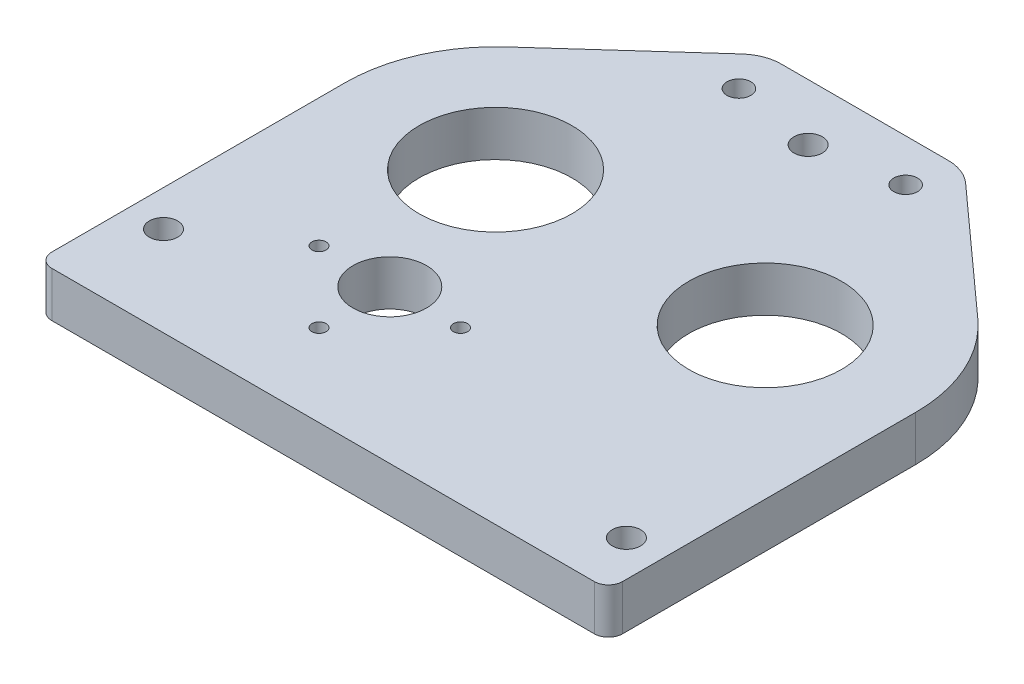
SolidWorks part; units mm, degrees
material "6061-T6 (SS)"
ref_plane "Front Plane" through (0, 0, 0) normal (0, 0, 1) x (1, 0, 0)
ref_plane "Top Plane" through (0, 0, 0) normal (0, 1, 0) x (1, 0, 0)
ref_plane "Right Plane" through (0, 0, 0) normal (1, 0, 0) x (0, 0, -1)
sketch "MasterSketch" plane through (0, 0, 0) normal (0, 1, 0) x (1, 0, 0)
  line L0 (-43.6583, 78.9815) -> (-8.5725, 27.2588) construction
  line L1 (-37.4522, 83.1914) -> (-2.3664, 31.4687)
  line L2 (-49.8644, 74.7716) -> (-14.7786, 23.0489)
  line L3 (15.24, 26.2031) -> (15.24, 177.1934) construction
  line L6 (-57.2127, 102.5887) -> (-52.8306, 72.5887)
  line L7 (-52.8306, 72.5887) -> (-3.3556, 79.8154)
  line L8 (-3.3556, 79.8154) -> (-14.1957, 154.0279)
  line L9 (-14.1957, 154.0279) -> (-57.2127, 102.5887)
  line L10 (-16.4304, 100.1391) -> (0.5118, 61.162) construction
  line L11 (-9.5528, 103.1286) -> (7.3895, 64.1515)
  line L12 (-23.308, 97.1496) -> (-6.3658, 58.1725)
  line L13 (74.1383, 78.9815) -> (39.0525, 27.2588) construction
  line L16 (-8.5725, 27.2588) -> (39.0525, 27.2588)
  line L17 (0, 0) -> (39.0525, 27.2588) construction
  line L18 (-8.5725, 27.2588) -> (0, 0) construction
  line L19 (-8.5725, 27.2588) -> (0.5118, 61.162) construction
  line L20 (67.9322, 83.1914) -> (32.8464, 31.4687)
  line L21 (-53.5533, 77.5362) -> (-43.6583, 78.9815) construction
  line L24 (-43.6583, 78.9815) -> (-42.9356, 74.034) construction
  line L25 (-6.5354, 101.5844) -> (-16.4304, 100.1391) construction
  line L26 (-16.4304, 100.1391) -> (-13.2506, 78.3701) construction
  line L27 (80.3444, 74.7716) -> (45.2586, 23.0489)
  line L28 (46.9104, 100.1391) -> (29.9682, 61.162) construction
  line L29 (40.0328, 103.1286) -> (23.0905, 64.1515)
  line L30 (53.788, 97.1496) -> (36.8458, 58.1725)
  line L31 (44.6757, 154.0279) -> (87.6927, 102.5887)
  line L32 (46.9104, 100.1391) -> (43.7306, 78.3701) construction
  line L33 (74.1383, 78.9815) -> (73.4156, 74.034) construction
  line L34 (84.0333, 77.5362) -> (74.1383, 78.9815) construction
  line L35 (33.8356, 79.8154) -> (44.6757, 154.0279)
  line L36 (83.3106, 72.5887) -> (33.8356, 79.8154)
  line L37 (87.6927, 102.5887) -> (83.3106, 72.5887)
  line L38 (0, 0) -> (0, -12.5) construction
  line L39 (-5.8229, 22.4963) -> (-3.0732, 27.2588)
  line L40 (-3.0732, 27.2588) -> (-5.8229, 32.0213)
  line L41 (-5.8229, 32.0213) -> (-11.3221, 32.0213)
  line L42 (-11.3221, 32.0213) -> (-14.0718, 27.2588)
  line L43 (-14.0718, 27.2588) -> (-11.3221, 22.4963)
  line L44 (-11.3221, 22.4963) -> (-5.8229, 22.4963)
  line L45 (36.3029, 32.0213) -> (33.5532, 27.2588)
  line L46 (33.5532, 27.2588) -> (36.3029, 22.4963)
  line L47 (36.3029, 22.4963) -> (41.8021, 22.4963)
  line L48 (41.8021, 22.4963) -> (44.5518, 27.2588)
  line L49 (44.5518, 27.2588) -> (41.8021, 32.0213)
  line L50 (41.8021, 32.0213) -> (36.3029, 32.0213)
  circle A0 centre (0, 0) radius 4.7625
  circle A1 centre (-8.5725, 27.2588) radius 23.8125
  circle A2 centre (39.0525, 27.2588) radius 23.8125
  arc A4 (-37.4522, 83.1914) -> (-49.8644, 74.7716) centre (-43.6583, 78.9815) ccw
  arc A5 (-14.7786, 23.0489) -> (-2.3664, 31.4687) centre (-8.5725, 27.2588) ccw
  arc A8 (-9.5528, 103.1286) -> (-23.308, 97.1496) centre (-16.4304, 100.1391) ccw
  arc A9 (-6.3658, 58.1725) -> (7.3895, 64.1515) centre (0.5118, 61.162) ccw
  circle A14 centre (-43.6583, 78.9815) radius 2.5
  circle A15 centre (-16.4304, 100.1391) radius 2.5
  arc A16 (67.9322, 83.1914) -> (80.3444, 74.7716) centre (74.1383, 78.9815) cw
  arc A17 (45.2586, 23.0489) -> (32.8464, 31.4687) centre (39.0525, 27.2588) cw
  arc A18 (40.0328, 103.1286) -> (53.788, 97.1496) centre (46.9104, 100.1391) cw
  arc A19 (36.8458, 58.1725) -> (23.0905, 64.1515) centre (29.9682, 61.162) cw
  circle A20 centre (46.9104, 100.1391) radius 2.5
  circle A21 centre (74.1383, 78.9815) radius 2.5
  circle A22 centre (0, 0) radius 17.5
  circle A23 centre (0, 0) radius 1.5875
  circle A24 centre (-8.5725, 27.2588) radius 4.7625 construction
  circle A25 centre (39.0525, 27.2588) radius 4.7625 construction
  circle A26 centre (0.5118, 61.162) radius 2.5
  circle A27 centre (29.9682, 61.162) radius 2.5
  circle A28 centre (-8.5725, 27.2588) radius 24.5999 construction
  circle A29 centre (39.0525, 27.2588) radius 24.5999 construction
  circle A30 centre (-8.5725, 27.2588) radius 13.5001
  circle A31 centre (39.0525, 27.2588) radius 13.5001
  circle A32 centre (0, 0) radius 12.5 construction
  circle A33 centre (0, -12.5) radius 1.25
  circle A34 centre (-12.5, 0) radius 1.25
  circle A35 centre (0, 12.5) radius 1.25
  circle A36 centre (12.5, 0) radius 1.25
  circle A37 centre (-8.5725, 27.2588) radius 5.4993 construction
  point P9 (-26.1154, 53.1202)
  point P17 (56.5954, 53.1202)
  point P20 (-7.9593, 80.6505)
  point P35 (38.4393, 80.6505)
  point P85 (-45.7828, 107.2521)
  point P86 (0, 0)
  point P87 (-35.3525, 111.2458)
  point P96 (0, 0)
  point P97 (2.3992, 158.8685)
  point P98 (-3.9444, 103.4277)
  point P99 (9.8129, 158.6502)
  point P101 (-2.264, 157.905)
  point P102 (-7.4628, 155.1245)
  point P103 (3.2548, 157.1392)
  point P104 (-5.1829, 156.7534)
  point P105 (-11.9901, 157.2295)
  point P106 (-13.7395, 163.021)
  point P107 (0.3824, 158.6677)
  point P108 (1.9033, 152.3194)
  point P109 (0.9424, 156.2031)
  point P110 (-13.2506, 154.0279)
  dimension "D1" = 47.625
  dimension "D2" = 9.525
  dimension "D5" = 2
  dimension "D7" = 3
  dimension "D13" = 35
  dimension "D14" = 3.175
  dimension "D15" = 9.525
  dimension "D16" = 5
  dimension "D17" = 49.1998
  dimension "D20" = 27.0002
  dimension "D21" = 25
  dimension "D23" = 2.5
  dimension "D3" = 75
  dimension "D4" = 50
  dimension "D6" = 75
  dimension "D8" = 10
  dimension "D9" = 5
  dimension "D10" = 10
  dimension "D11" = 62.5
  dimension "D12" = 22
  dimension "D18" = 42.5
  dimension "D19" = 30
  dimension "D22" = 4
sketch "Sketch1" plane through (0, 0, 0) normal (0, 1, 0) x (1, 0, 0)
  line L0 (-35.1724, 27.2588) -> (-35.1724, -27.025)
  line L1 (-35.1724, -27.025) -> (65.6524, -27.025)
  line L2 (65.6524, -27.025) -> (65.6524, 27.2588)
  line L3 (-26.3819, 47.0169) -> (-4.5091, 66.7324)
  line L4 (0.5118, 68.6613) -> (29.9682, 68.6613)
  line L5 (34.9891, 66.7324) -> (56.8619, 47.0169)
  line L6 (15.24, -199973.7969) -> (15.24, 200177.1934) construction
  line L7 (-35.1724, -11.15) -> (-28.8224, -11.15) construction
  line L8 (-28.8224, -11.15) -> (-28.8224, -20.675) construction
  line L9 (65.6524, -17.5) -> (59.3024, -17.5) construction
  line L10 (59.3024, -17.5) -> (59.3024, -27.025) construction
  line L11 (15.24, 68.6613) -> (15.24, 58.6613) construction
  line L12 (-28.8224, -17.5) -> (0, -17.5) construction
  circle A1 centre (0, 0) radius 17.5 construction
  circle A2 centre (-8.5725, 27.2588) radius 26.5999
  arc A3 (-26.3819, 47.0169) -> (-35.1724, 27.2588) centre (-8.5725, 27.2588) ccw
  circle A4 centre (-8.5725, 27.2588) radius 13.5001
  arc A5 (0.5118, 68.6613) -> (-4.5091, 66.7324) centre (0.5118, 61.162) ccw
  circle A6 centre (39.0525, 27.2588) radius 26.5999
  arc A7 (65.6524, 27.2588) -> (56.8619, 47.0169) centre (39.0525, 27.2588) ccw
  arc A8 (34.9891, 66.7324) -> (29.9682, 68.6613) centre (29.9682, 61.162) ccw
  arc A9 (-6.3658, 58.1725) -> (7.3895, 64.1515) centre (0.5118, 61.162) ccw construction
  arc A10 (23.0905, 64.1515) -> (36.8458, 58.1725) centre (29.9682, 61.162) ccw construction
  circle A11 centre (39.0525, 27.2588) radius 13.5001
  circle A12 centre (-8.5725, 27.2588) radius 13.5001 construction
  circle A14 centre (0, 0) radius 6.5
  circle A16 centre (0.5118, 61.162) radius 2.1
  circle A17 centre (29.9682, 61.162) radius 2.1
  circle A18 centre (-28.8224, -11.15) radius 2.5
  circle A19 centre (59.3024, -17.5) radius 2.5
  circle A20 centre (15.24, 58.6613) radius 2.5
  circle A21 centre (-28.8224, -11.15) radius 6.35 construction
  circle A23 centre (12.5, 0) radius 1.25 construction
  circle A24 centre (0, -12.5) radius 1.25 construction
  circle A25 centre (-12.5, 0) radius 1.25 construction
  circle A27 centre (12.5, 0) radius 1.25
  circle A28 centre (0, -12.5) radius 1.25
  circle A29 centre (-12.5, 0) radius 1.25
  point P1 (-28.8224, -11.15)
  point P51 (-28.8224, -17.5)
  point P64 (-28.8224, -17.5)
  point P65 (0, 0)
  dimension "D3" = 13
  dimension "D4" = 4.2
  dimension "D5" = 5
  dimension "D6" = 12.7
  dimension "D8" = 5
  dimension "D7" = 10
  dimension "D9" = 9.525
  dimension "D1" = 2
  dimension "D2" = 2
extrude "Boss-Extrude1" add sketch "Sketch1" along normal blind 8.001
fillet "Fillet1" radius 2.5 2 edges at (65.6524, 4.0005, 27.025) (-35.1724, 4.0005, 27.025)
